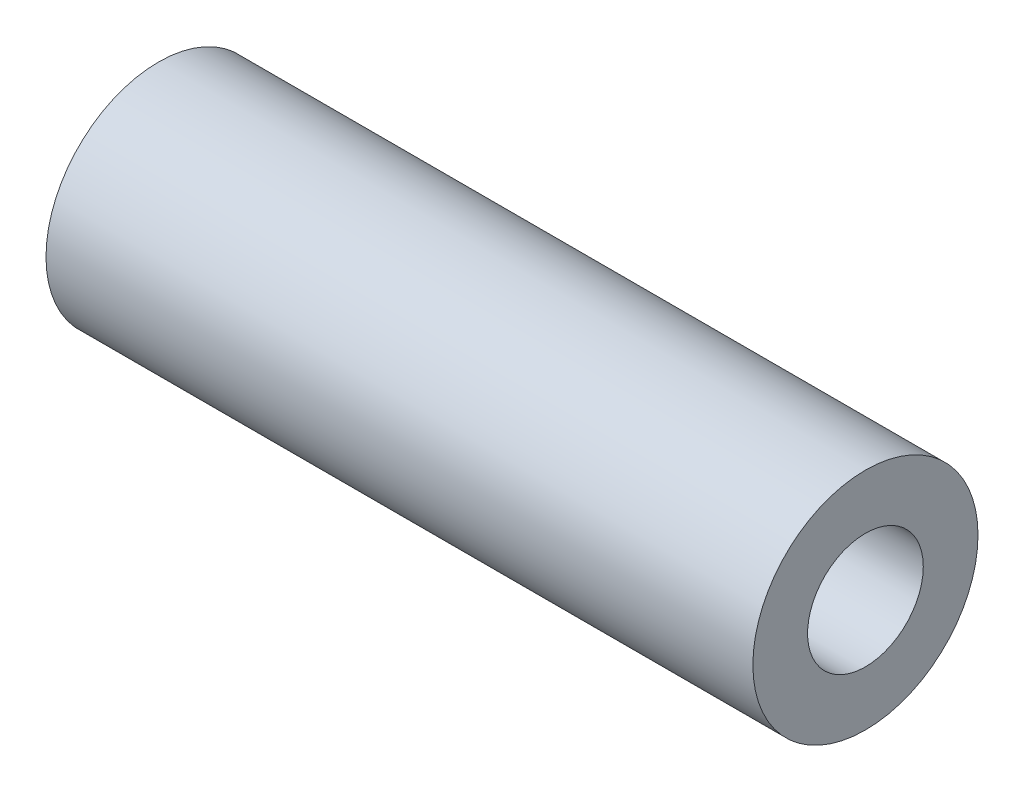
SolidWorks part; units mm, degrees
material "6063-T5"
ref_plane "Front" through (0, 0, 0) normal (0, 0, 1) x (1, 0, 0)
ref_plane "Top" through (0, 0, 0) normal (0, 1, 0) x (1, 0, 0)
ref_plane "Right" through (0, 0, 0) normal (1, 0, 0) x (0, 0, -1)
sketch "Sketch1" plane through (0, 0, 0) normal (1, 0, 0) x (0, 0, -1)
  circle A0 centre (0, 0) radius 3.2639
  circle A1 centre (0, 0) radius 6.35
  dimension "D1" = 12.7
  dimension "D2" = 6.5278
extrude "Boss-Extrude1" add sketch "Sketch1" along normal blind 39.878
